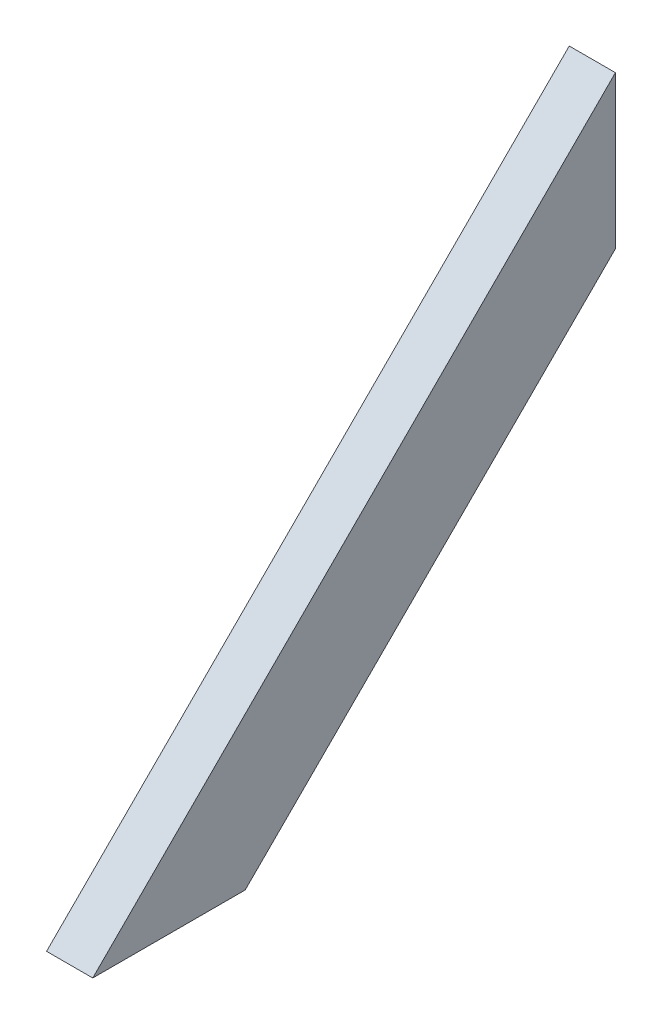
SolidWorks part; units mm, degrees
material "Pine"
ref_plane "Front Plane" through (0, 0, 0) normal (0, 0, 1) x (1, 0, 0)
ref_plane "Top Plane" through (0, 0, 0) normal (0, 1, 0) x (1, 0, 0)
ref_plane "Right Plane" through (0, 0, 0) normal (1, 0, 0) x (0, 0, -1)
sketch "Sketch1" plane through (0, 0, 0) normal (1, 0, 0) x (0, 0, -1)
  line L0 (0, 0) -> (125.7236, 0)
  line L1 (125.7236, 0) -> (431.0523, 305.3287)
  line L2 (431.0523, 305.3287) -> (431.0523, 431.0523)
  line L3 (431.0523, 431.0523) -> (0, 0)
  dimension "D1" = 88.9
  dimension "D2" = 609.6
  dimension "D3" = 45
extrude "Boss-Extrude1" add sketch "Sketch1" along normal blind 38.1
